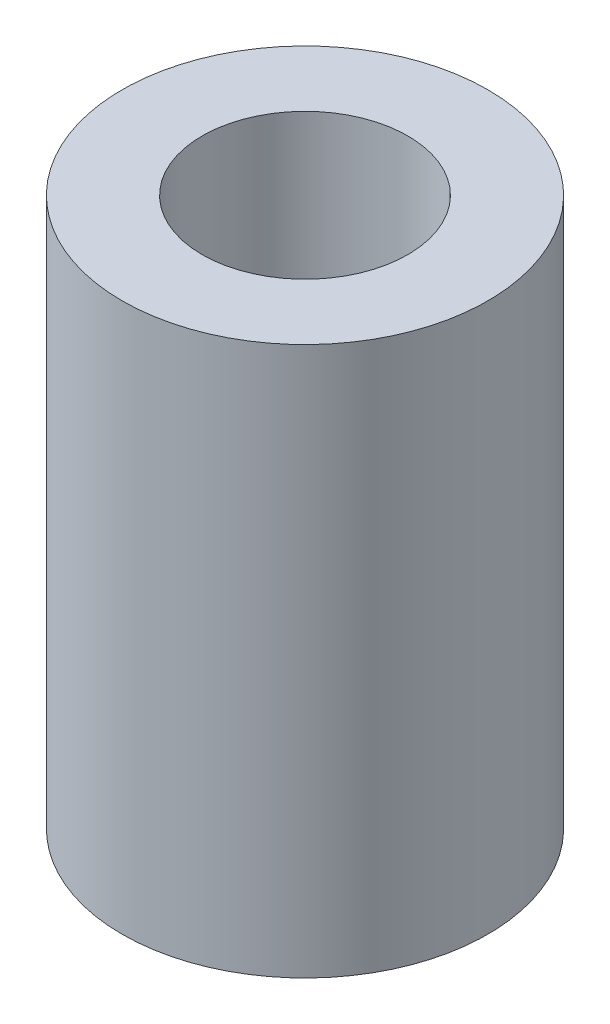
SolidWorks part; units mm, degrees
ref_plane "Front" through (0, 0, 0) normal (0, 0, 1) x (1, 0, 0)
ref_plane "Top" through (0, 0, 0) normal (0, 1, 0) x (1, 0, 0)
ref_plane "Right" through (0, 0, 0) normal (1, 0, 0) x (0, 0, -1)
sketch "Sketch1" plane through (0, 0, 0) normal (0, 1, 0) x (1, 0, 0)
  circle A0 centre (0, 0) radius 2.25
  circle A1 centre (0, 0) radius 4
  dimension "D1" = 4.5
extrude "Boss-Extrude1" add sketch "Sketch1" along normal blind 12
